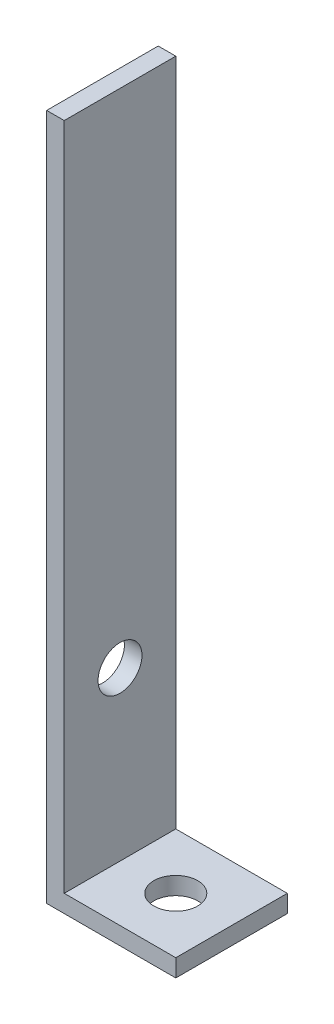
SolidWorks part; units mm, degrees
ref_plane "Front Plane" through (0, 0, 0) normal (0, 0, 1) x (1, 0, 0)
ref_plane "Top Plane" through (0, 0, 0) normal (0, 1, 0) x (1, 0, 0)
ref_plane "Right Plane" through (0, 0, 0) normal (1, 0, 0) x (0, 0, -1)
sketch "Sketch1" plane through (0, 0, 0) normal (0, 0, 1) x (1, 0, 0)
  line L1 (0, 0) -> (14.7, 0)
  line L2 (0, 0) -> (0, 2)
  line L3 (0, 2) -> (14.7, 2)
  line L4 (14.7, 0) -> (14.7, 2)
  line L5 (0, 2) -> (2, 2)
  line L6 (0, 2) -> (0, 78.2)
  line L7 (0, 78.2) -> (2, 78.2)
  line L8 (2, 2) -> (2, 78.2)
  dimension "D1" = 2
  dimension "D2" = 12.7
  dimension "D3" = 76.2
extrude "Boss-Extrude1" add sketch "Sketch1" along normal blind 12.7 contours L1 L4 L3 L2 | L6 L5 L8 L7
hole_wizard "Ø5.0mm Dowel Hole1" positions "Sketch2" profile "Sketch3" hole size "Ø5.0" standard "ANSI Metric" end condition through all
sketch "Sketch2" plane through (2, 0, 0) normal (1, 0, 0) x (0, 0, -1)
  line L0 (-12.7, 78.2) -> (0, 78.2) construction
  line L1 (-12.7, 2) -> (0, 2) construction
  point P0 (-6.35, 21.05)
  point P5 (-6.35, 78.2)
  dimension "D1" = 19.05
sketch "Sketch3" plane through (2, 21.05, 6.35) normal (0, 1, 0) x (0, 0, -1)
  line L0 (0, 0) -> (0, 2)
  line L1 (0, 2) -> (2.5, 2)
  line L2 (2.5, 2) -> (2.5, 0)
  line L5 (2.5, 0) -> (0, 0)
  line L11 (0, -6.35) -> (0, 107.95) construction
  dimension "Thru Hole Dia." = 5
  dimension "Thru Hole Depth" = 2
hole_wizard "Ø5.0mm Dowel Hole2" positions "Sketch4" profile "Sketch5" hole size "Ø5.0" standard "ANSI Metric" end condition through all
sketch "Sketch4" plane through (0, 2, 0) normal (0, 1, 0) x (1, 0, 0)
  line L0 (2, -12.7) -> (14.7, -12.7) construction
  line L1 (14.7, -12.7) -> (14.7, 0) construction
  point P0 (8.35, -6.35)
  point P5 (8.35, -12.7)
  point P8 (14.7, -6.35)
sketch "Sketch5" plane through (8.35, 2, 6.35) normal (1, 0, 0) x (0, 0, 1)
  line L0 (0, 0) -> (0, 2)
  line L1 (0, 2) -> (2.5, 2)
  line L2 (2.5, 2) -> (2.5, 0)
  line L5 (2.5, 0) -> (0, 0)
  line L11 (0, -6.35) -> (0, 107.95) construction
  dimension "Thru Hole Dia." = 5
  dimension "Thru Hole Depth" = 2
